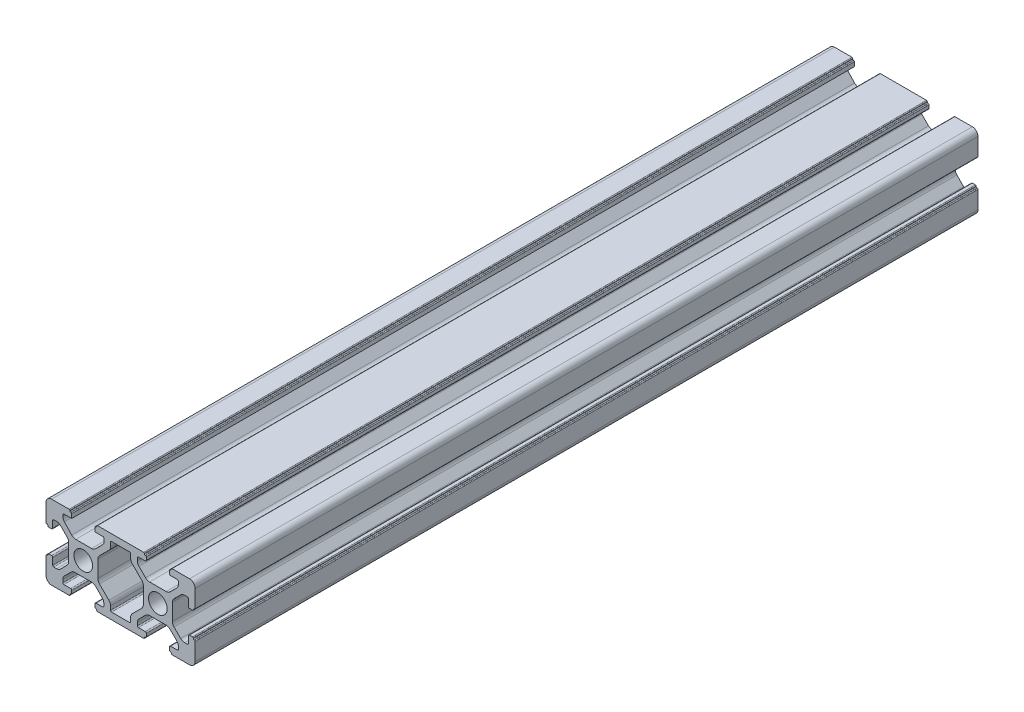
SolidWorks part; units mm, degrees
material "6063-O"
ref_plane "Front Plane" through (0, 0, 0) normal (0, 0, 1) x (1, 0, 0)
ref_plane "Top Plane" through (0, 0, 0) normal (0, 1, 0) x (1, 0, 0)
ref_plane "Right Plane" through (0, 0, 0) normal (1, 0, 0) x (0, 0, -1)
sketch "Sketch1" plane through (0, 0, 0) normal (0, 0, 1) x (1, 0, 0)
  line L0 (1.5, 0) -> (6.2, 0)
  line L1 (40, 1.5) -> (40, 6.2)
  line L2 (38.5, 20) -> (33.8, 20)
  line L3 (0, 18.5) -> (0, 13.8)
  line L4 (17.6, 1.8) -> (22.4, 1.8)
  line L5 (32.218, 13.9) -> (27.782, 13.9)
  line L6 (26.1, 12.218) -> (26.1, 7.782)
  line L7 (17.6, 18.2) -> (22.4, 18.2)
  line L8 (12.218, 13.9) -> (7.9864, 13.9)
  line L9 (6.1, 12.218) -> (6.1, 7.782)
  line L10 (7.782, 6.1) -> (12.218, 6.1)
  line L11 (13.9, 7.782) -> (13.9, 12.218)
  line L12 (27.782, 6.1) -> (32.218, 6.1)
  line L13 (33.9, 7.782) -> (33.9, 12.218)
  line L14 (26.7213, 14.3393) -> (24.9393, 16.1213)
  line L15 (33.2787, 14.3393) -> (35.0607, 16.1213)
  line L16 (34.3393, 13.2787) -> (36.1213, 15.0607)
  line L17 (25.6607, 6.7213) -> (23.1393, 4.2)
  line L18 (15.2, 1.8) -> (13.4, 1.8)
  line L19 (26.7213, 5.6607) -> (24.9393, 3.8787)
  line L20 (24.8, 1.8) -> (26.6, 1.8)
  line L21 (15.3, 18.2) -> (13.1, 18.2)
  line L22 (13.2787, 14.3393) -> (15.1607, 16.2213)
  line L23 (14.3393, 13.2787) -> (16.8607, 15.8)
  line L24 (5.6607, 6.7213) -> (3.8787, 4.9393)
  line L25 (6.7213, 5.6607) -> (4.9393, 3.8787)
  line L26 (6.897, 14.3689) -> (4.9106, 16.4674)
  line L27 (5.6607, 13.2787) -> (3.8787, 15.0607)
  line L28 (14.3393, 6.7213) -> (16.8607, 4.2)
  line L29 (13.2787, 5.6607) -> (15.0607, 3.8787)
  line L30 (24.8, 18.2) -> (26.6, 18.2)
  line L31 (25.6607, 13.2787) -> (23.1393, 15.8)
  line L32 (34.3393, 6.7213) -> (36.1213, 4.9393)
  line L33 (33.2787, 5.6607) -> (35.0607, 3.8787)
  line L34 (1.8, 15.2) -> (1.8, 13.4)
  line L35 (24.5, 2.1) -> (24.5, 2.818)
  line L36 (4.5, 2.1) -> (4.5, 2.818)
  line L37 (2.818, 4.5) -> (2.1, 4.5)
  line L38 (4.5, 17.9) -> (4.5, 17.4986)
  line L39 (2.818, 15.5) -> (2.1, 15.5)
  line L40 (15.6, 17.9) -> (15.6, 17.282)
  line L41 (15.5, 2.818) -> (15.5, 2.1)
  line L42 (38.2, 15.2) -> (38.2, 13.4)
  line L43 (35.5, 2.818) -> (35.5, 2.1)
  line L44 (37.182, 4.5) -> (37.9, 4.5)
  line L45 (35.5, 17.182) -> (35.5, 17.9)
  line L46 (37.182, 15.5) -> (37.9, 15.5)
  line L47 (17.3, 2.1) -> (17.3, 3.1393)
  line L48 (22.7, 2.1) -> (22.7, 3.1393)
  line L49 (17.3, 17.9) -> (17.3, 16.8607)
  line L50 (22.7, 17.9) -> (22.7, 16.8607)
  line L51 (24.5, 17.9) -> (24.5, 17.182)
  line L52 (6.9, 19.3) -> (6.9, 18.2)
  line L53 (13.1, 19.3) -> (13.1, 18.2)
  line L54 (6.9, 1.5) -> (6.9, 0.7)
  line L55 (13.1, 1.5) -> (13.1, 0.7)
  line L56 (13.8, 0) -> (26.2, 0)
  line L57 (6.6, 1.8) -> (4.8, 1.8)
  line L58 (6.9, 18.2) -> (4.8, 18.2)
  line L59 (6.2, 20) -> (1.5, 20)
  line L60 (39.3, 6.9) -> (38.5, 6.9)
  line L61 (39.3, 13.1) -> (38.5, 13.1)
  line L62 (1.5, 13.1) -> (0.7, 13.1)
  line L63 (1.5, 6.9) -> (0.7, 6.9)
  line L64 (0, 6.2) -> (0, 1.5)
  line L65 (1.8, 6.6) -> (1.8, 4.8)
  line L66 (38.2, 6.6) -> (38.2, 4.8)
  line L67 (40, 13.8) -> (40, 18.5)
  line L68 (33.1, 19.3) -> (33.1, 18.5)
  line L69 (26.9, 19.3) -> (26.9, 18.5)
  line L70 (26.9, 1.5) -> (26.9, 0.7)
  line L71 (33.1, 1.5) -> (33.1, 0.7)
  line L72 (33.8, 0) -> (38.5, 0)
  line L73 (33.4, 1.8) -> (35.2, 1.8)
  line L74 (26.2, 20) -> (13.8, 20)
  line L75 (33.4, 18.2) -> (35.2, 18.2)
  line L76 (6.7, 0.5) -> (6.6, 0.5)
  line L77 (6.4, 0.3) -> (6.4, 0.2)
  line L78 (13.3, 0.5) -> (13.4, 0.5)
  line L79 (13.6, 0.3) -> (13.6, 0.2)
  line L80 (26.7, 0.5) -> (26.6, 0.5)
  line L81 (26.4, 0.3) -> (26.4, 0.2)
  line L82 (33.3, 0.5) -> (33.4, 0.5)
  line L83 (33.6, 0.3) -> (33.6, 0.2)
  line L85 (6.4, 19.8) -> (6.4, 19.7)
  line L86 (6.6, 19.5) -> (6.7, 19.5)
  line L87 (13.6, 19.8) -> (13.6, 19.7)
  line L88 (13.4, 19.5) -> (13.3, 19.5)
  line L89 (26.4, 19.8) -> (26.4, 19.7)
  line L90 (26.6, 19.5) -> (26.7, 19.5)
  line L91 (33.6, 19.8) -> (33.6, 19.7)
  line L92 (33.4, 19.5) -> (33.3, 19.5)
  line L93 (0.5, 13.3) -> (0.5, 13.4)
  line L94 (0.3, 13.6) -> (0.2, 13.6)
  line L95 (0.5, 6.7) -> (0.5, 6.6)
  line L96 (0.3, 6.4) -> (0.2, 6.4)
  line L97 (39.5, 13.3) -> (39.5, 13.4)
  line L98 (39.7, 13.6) -> (39.8, 13.6)
  line L99 (39.5, 6.7) -> (39.5, 6.6)
  line L100 (39.7, 6.4) -> (39.8, 6.4)
  circle A0 centre (10, 10) radius 2.5
  circle A1 centre (30, 10) radius 2.5
  arc A2 (38.5, 0) -> (40, 1.5) centre (38.5, 1.5) ccw
  arc A3 (40, 18.5) -> (38.5, 20) centre (38.5, 18.5) ccw
  arc A4 (1.5, 0) -> (0, 1.5) centre (1.5, 1.5) cw
  arc A5 (1.5, 20) -> (0, 18.5) centre (1.5, 18.5) ccw
  arc A6 (26.7213, 5.6607) -> (27.782, 6.1) centre (27.782, 4.6) cw
  arc A7 (32.218, 6.1) -> (33.2787, 5.6607) centre (32.218, 4.6) cw
  arc A8 (33.9, 7.782) -> (34.3393, 6.7213) centre (35.4, 7.782) ccw
  arc A9 (33.2787, 14.3393) -> (32.218, 13.9) centre (32.218, 15.4) cw
  arc A10 (14.3393, 6.7213) -> (13.9, 7.782) centre (15.4, 7.782) cw
  arc A11 (14.3393, 13.2787) -> (13.9, 12.218) centre (15.4, 12.218) ccw
  arc A12 (25.6607, 6.7213) -> (26.1, 7.782) centre (24.6, 7.782) ccw
  arc A13 (26.1, 12.218) -> (25.6607, 13.2787) centre (24.6, 12.218) ccw
  arc A14 (27.782, 13.9) -> (26.7213, 14.3393) centre (27.782, 15.4) cw
  arc A15 (5.6607, 13.2787) -> (6.1, 12.218) centre (4.6, 12.218) cw
  arc A16 (5.6607, 6.7213) -> (6.1, 7.782) centre (4.6, 7.782) ccw
  arc A17 (13.2787, 5.6607) -> (12.218, 6.1) centre (12.218, 4.6) ccw
  arc A18 (6.7213, 5.6607) -> (7.782, 6.1) centre (7.782, 4.6) cw
  arc A19 (13.2787, 14.3393) -> (12.218, 13.9) centre (12.218, 15.4) cw
  arc A20 (6.897, 14.3689) -> (7.9864, 13.9) centre (7.9864, 15.4) ccw
  arc A21 (36.1213, 4.9393) -> (37.182, 4.5) centre (37.182, 6) ccw
  arc A22 (36.1213, 15.0607) -> (37.182, 15.5) centre (37.182, 14) cw
  arc A23 (35.0607, 16.1213) -> (35.5, 17.182) centre (34, 17.182) ccw
  arc A24 (24.5, 17.182) -> (24.9393, 16.1213) centre (26, 17.182) ccw
  arc A25 (22.7, 16.8607) -> (23.1393, 15.8) centre (24.2, 16.8607) ccw
  arc A26 (17.3, 16.8607) -> (16.8607, 15.8) centre (15.8, 16.8607) cw
  arc A27 (4.9106, 16.4674) -> (4.5, 17.4986) centre (6, 17.4986) cw
  arc A28 (15.6, 17.282) -> (15.1607, 16.2213) centre (14.1, 17.282) cw
  arc A29 (3.8787, 15.0607) -> (2.818, 15.5) centre (2.818, 14) ccw
  arc A30 (3.8787, 4.9393) -> (2.818, 4.5) centre (2.818, 6) cw
  arc A31 (4.9393, 3.8787) -> (4.5, 2.818) centre (6, 2.818) ccw
  arc A32 (35.0607, 3.8787) -> (35.5, 2.818) centre (34, 2.818) cw
  arc A33 (24.9393, 3.8787) -> (24.5, 2.818) centre (26, 2.818) ccw
  arc A34 (22.7, 3.1393) -> (23.1393, 4.2) centre (24.2, 3.1393) cw
  arc A35 (17.3, 3.1393) -> (16.8607, 4.2) centre (15.8, 3.1393) ccw
  arc A36 (15.5, 2.818) -> (15.0607, 3.8787) centre (14, 2.818) ccw
  arc A37 (1.8, 6.6) -> (1.5, 6.9) centre (1.5, 6.6) ccw
  arc A38 (1.8, 13.4) -> (1.5, 13.1) centre (1.5, 13.4) cw
  arc A39 (17.6, 18.2) -> (17.3, 17.9) centre (17.6, 17.9) ccw
  arc A40 (22.4, 1.8) -> (22.7, 2.1) centre (22.4, 2.1) ccw
  arc A41 (17.6, 1.8) -> (17.3, 2.1) centre (17.6, 2.1) cw
  arc A42 (15.2, 1.8) -> (15.5, 2.1) centre (15.2, 2.1) ccw
  arc A43 (6.6, 1.8) -> (6.9, 1.5) centre (6.6, 1.5) cw
  arc A44 (13.4, 1.8) -> (13.1, 1.5) centre (13.4, 1.5) ccw
  arc A45 (24.8, 1.8) -> (24.5, 2.1) centre (24.8, 2.1) cw
  arc A46 (35.2, 1.8) -> (35.5, 2.1) centre (35.2, 2.1) ccw
  arc A47 (26.6, 1.8) -> (26.9, 1.5) centre (26.6, 1.5) cw
  arc A48 (33.4, 1.8) -> (33.1, 1.5) centre (33.4, 1.5) ccw
  arc A49 (26.9, 18.5) -> (26.6, 18.2) centre (26.6, 18.5) cw
  arc A50 (33.1, 18.5) -> (33.4, 18.2) centre (33.4, 18.5) ccw
  arc A51 (37.9, 4.5) -> (38.2, 4.8) centre (37.9, 4.8) ccw
  arc A52 (38.5, 13.1) -> (38.2, 13.4) centre (38.5, 13.4) cw
  arc A53 (38.5, 6.9) -> (38.2, 6.6) centre (38.5, 6.6) ccw
  arc A54 (38.2, 15.2) -> (37.9, 15.5) centre (37.9, 15.2) ccw
  arc A55 (35.2, 18.2) -> (35.5, 17.9) centre (35.2, 17.9) cw
  arc A56 (24.8, 18.2) -> (24.5, 17.9) centre (24.8, 17.9) ccw
  arc A57 (22.4, 18.2) -> (22.7, 17.9) centre (22.4, 17.9) cw
  arc A58 (15.3, 18.2) -> (15.6, 17.9) centre (15.3, 17.9) cw
  arc A59 (4.5, 17.9) -> (4.8, 18.2) centre (4.8, 17.9) cw
  arc A60 (1.8, 15.2) -> (2.1, 15.5) centre (2.1, 15.2) cw
  arc A61 (1.8, 4.8) -> (2.1, 4.5) centre (2.1, 4.8) ccw
  arc A62 (4.5, 2.1) -> (4.8, 1.8) centre (4.8, 2.1) ccw
  arc A63 (34.3393, 13.2787) -> (33.9, 12.218) centre (35.4, 12.218) ccw
  arc A64 (6.4, 0.2) -> (6.2, 0) centre (6.2, 0.2) cw
  arc A65 (6.6, 0.5) -> (6.4, 0.3) centre (6.6, 0.3) ccw
  arc A66 (6.7, 0.5) -> (6.9, 0.7) centre (6.7, 0.7) ccw
  arc A67 (13.6, 0.2) -> (13.8, 0) centre (13.8, 0.2) ccw
  arc A68 (13.4, 0.5) -> (13.6, 0.3) centre (13.4, 0.3) cw
  arc A69 (13.3, 0.5) -> (13.1, 0.7) centre (13.3, 0.7) cw
  arc A70 (26.4, 0.2) -> (26.2, 0) centre (26.2, 0.2) cw
  arc A71 (26.6, 0.5) -> (26.4, 0.3) centre (26.6, 0.3) ccw
  arc A72 (26.7, 0.5) -> (26.9, 0.7) centre (26.7, 0.7) ccw
  arc A73 (33.6, 0.2) -> (33.8, 0) centre (33.8, 0.2) ccw
  arc A74 (33.4, 0.5) -> (33.6, 0.3) centre (33.4, 0.3) cw
  arc A75 (33.3, 0.5) -> (33.1, 0.7) centre (33.3, 0.7) cw
  arc A76 (39.8, 6.4) -> (40, 6.2) centre (39.8, 6.2) cw
  arc A77 (39.5, 6.6) -> (39.7, 6.4) centre (39.7, 6.6) ccw
  arc A78 (39.5, 6.7) -> (39.3, 6.9) centre (39.3, 6.7) ccw
  arc A79 (39.5, 13.3) -> (39.3, 13.1) centre (39.3, 13.3) cw
  arc A80 (39.5, 13.4) -> (39.7, 13.6) centre (39.7, 13.4) cw
  arc A81 (39.8, 13.6) -> (40, 13.8) centre (39.8, 13.8) ccw
  arc A82 (33.3, 19.5) -> (33.1, 19.3) centre (33.3, 19.3) ccw
  arc A83 (33.6, 19.7) -> (33.4, 19.5) centre (33.4, 19.7) cw
  arc A84 (33.6, 19.8) -> (33.8, 20) centre (33.8, 19.8) cw
  arc A85 (26.7, 19.5) -> (26.9, 19.3) centre (26.7, 19.3) cw
  arc A86 (26.4, 19.7) -> (26.6, 19.5) centre (26.6, 19.7) ccw
  arc A87 (26.4, 19.8) -> (26.2, 20) centre (26.2, 19.8) ccw
  arc A88 (0.2, 6.4) -> (0, 6.2) centre (0.2, 6.2) ccw
  arc A89 (0.5, 6.6) -> (0.3, 6.4) centre (0.3, 6.6) cw
  arc A90 (0.5, 6.7) -> (0.7, 6.9) centre (0.7, 6.7) cw
  arc A91 (13.3, 19.5) -> (13.1, 19.3) centre (13.3, 19.3) ccw
  arc A92 (13.6, 19.7) -> (13.4, 19.5) centre (13.4, 19.7) cw
  arc A93 (13.6, 19.8) -> (13.8, 20) centre (13.8, 19.8) cw
  arc A94 (6.2, 20) -> (6.4, 19.8) centre (6.2, 19.8) cw
  arc A95 (6.7, 19.5) -> (6.9, 19.3) centre (6.7, 19.3) cw
  arc A96 (6.4, 19.7) -> (6.6, 19.5) centre (6.6, 19.7) ccw
  arc A97 (0.5, 13.3) -> (0.7, 13.1) centre (0.7, 13.3) ccw
  arc A98 (0.2, 13.6) -> (0, 13.8) centre (0.2, 13.8) cw
  arc A99 (0.5, 13.4) -> (0.3, 13.6) centre (0.3, 13.4) ccw
  point P87 (0, 0)
  point P178 (1.8, 6.9)
  point P181 (1.8, 13.1)
  point P186 (22.7, 1.8)
  point P193 (6.9, 1.8)
  point P204 (33.1, 1.8)
  point P209 (33.1, 18.2)
  point P216 (38.2, 6.9)
  point P243 (6.9, 0.5)
  point P248 (13.6, 0.5)
  point P257 (26.9, 0.5)
extrude "Boss-Extrude2" add sketch "Sketch1" along normal blind 210 contours A57 L7 A39 L49 A26 L23 A11 L11 A10 L28 A35 L47 A41 L4 A40 L48 A34 L17 A12 L6 A13 L31 A25 L50 | A0 | A1 | L59 A5 L3 A98 L94 A99 L93 A97 L62 A38 L34 A60 L39 A29 L27 A15 L9 A16 L24 A30 L37 A61 L65 A37 L63 A90 L95 A89 L96 A88 L64 A4 L0 A64 L77 A65 L76 A66 L54 A43 L57 A62 L36 A31 L25 A18 L10 A17 L29 A36 L41 A42 L18 A44 L55 A69 L78 A68 L79 A67 L56 A70 L81 A71 L80 A72 L70 A47 L20 A45 L35 A33 L19 A6 L12 A7 L33 A32 L43 A46 L73 A48 L71 A75 L82 A74 L83 A73 L72 A2 L1 A76 L100 A77 L99 A78 L60 A53 L66 A51 L44 A21 L32 A8 L13 A63 L16 A22 L46 A54 L42 A52 L61 A79 L97 A80 L98 A81 L67 A3 L2 A84 L91 A83 L92 A82 L68 A50 L75 A55 L45 A23 L15 A9 L5 A14 L14 A24 L51 A56 L30 A49 L69 A85 L90 A86 L89 A87 L74 A93 L87 A92 L88 A91 L53 L21 A58 L40 A28 L22 A19 L8 A20 L26 A27 L38 A59 L58 L52 A95 L86 A96 L85 A94
